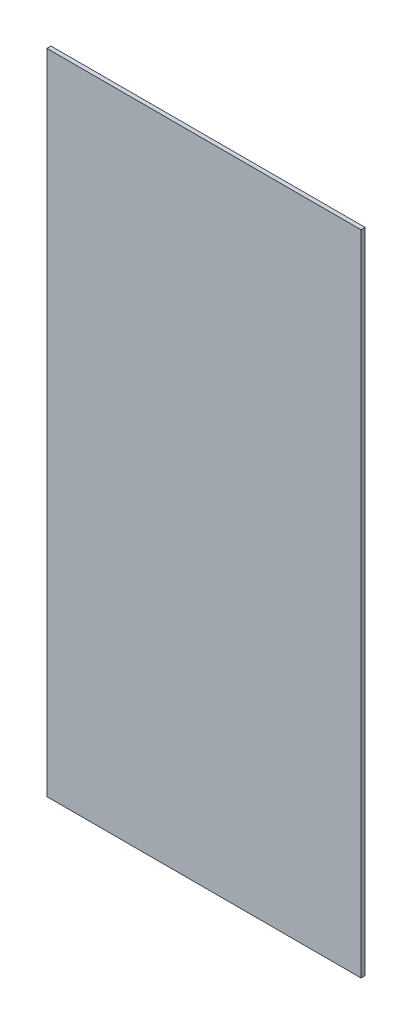
SolidWorks part; units mm, degrees
ref_plane "Front Plane" through (0, 0, 0) normal (0, 0, 1) x (1, 0, 0)
ref_plane "Top Plane" through (0, 0, 0) normal (0, 1, 0) x (1, 0, 0)
ref_plane "Right Plane" through (0, 0, 0) normal (1, 0, 0) x (0, 0, -1)
sketch "Sketch1" plane through (0, 0, 0) normal (0, 0, 1) x (1, 0, 0)
  line L1 (0, 0) -> (1219.2, 0)
  line L2 (0, 0) -> (0, 2514.6)
  line L3 (0, 2514.6) -> (1219.2, 2514.6)
  line L4 (1219.2, 0) -> (1219.2, 2514.6)
  dimension "D1" = 2514.6
  dimension "D2" = 1219.2
extrude "Boss-Extrude1" add sketch "Sketch1" along normal blind 15.875
